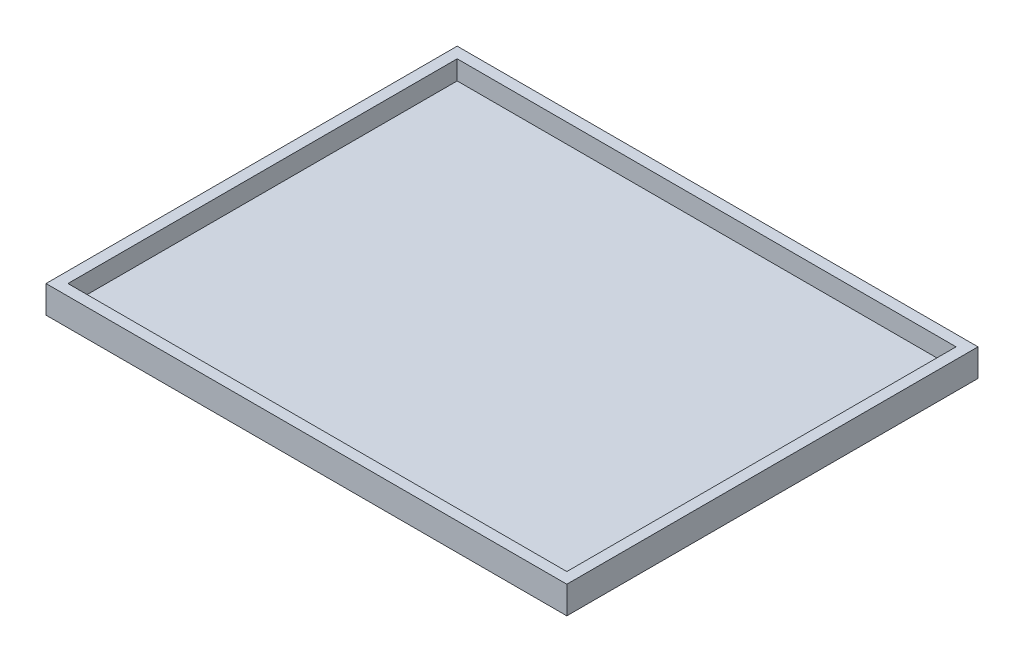
SolidWorks part; units mm, degrees
ref_plane "前视基准面" through (0, 0, 0) normal (0, 0, 1) x (1, 0, 0)
ref_plane "上视基准面" through (0, 0, 0) normal (0, 1, 0) x (1, 0, 0)
ref_plane "右视基准面" through (0, 0, 0) normal (1, 0, 0) x (0, 0, -1)
other "Configuration Table"
sketch "草图6" plane through (0, 0, 0) normal (0, 1, 0) x (1, 0, 0)
  line L1 (-103.2333, 63.8083) -> (-8.2333, 63.8083)
  line L2 (-103.2333, 63.8083) -> (-103.2333, -11.1917)
  line L3 (-103.2333, -11.1917) -> (-8.2333, -11.1917)
  line L4 (-8.2333, 63.8083) -> (-8.2333, -11.1917)
  line L5 (-103.2333, 63.8083) -> (-8.2333, -11.1917) construction
  line L6 (-103.2333, -11.1917) -> (-8.2333, 63.8083) construction
  point P0 (-55.7333, 26.3083)
  dimension "D1" = 95
  dimension "D2" = 75
extrude "凸台-拉伸1" add sketch "草图6" along normal blind 5
sketch "草图7" plane through (0, 5, 0) normal (0, 1, 0) x (1, 0, 0)
  line L8 (-10.2333, -9.1917) -> (-10.2333, 61.8083)
  line L9 (-10.2333, 61.8083) -> (-101.2333, 61.8083)
  line L10 (-101.2333, 61.8083) -> (-101.2333, -9.1917)
  line L11 (-101.2333, -9.1917) -> (-10.2333, -9.1917)
  line L12 (-10.2333, -9.1917) -> (-10.2333, 61.8083)
  line L13 (-10.2333, 61.8083) -> (-101.2333, 61.8083)
  line L14 (-101.2333, 61.8083) -> (-101.2333, -9.1917)
  line L15 (-101.2333, -9.1917) -> (-10.2333, -9.1917)
  dimension "D1" = 2
extrude "切除-拉伸1" cut sketch "草图7" against normal blind 3.5
